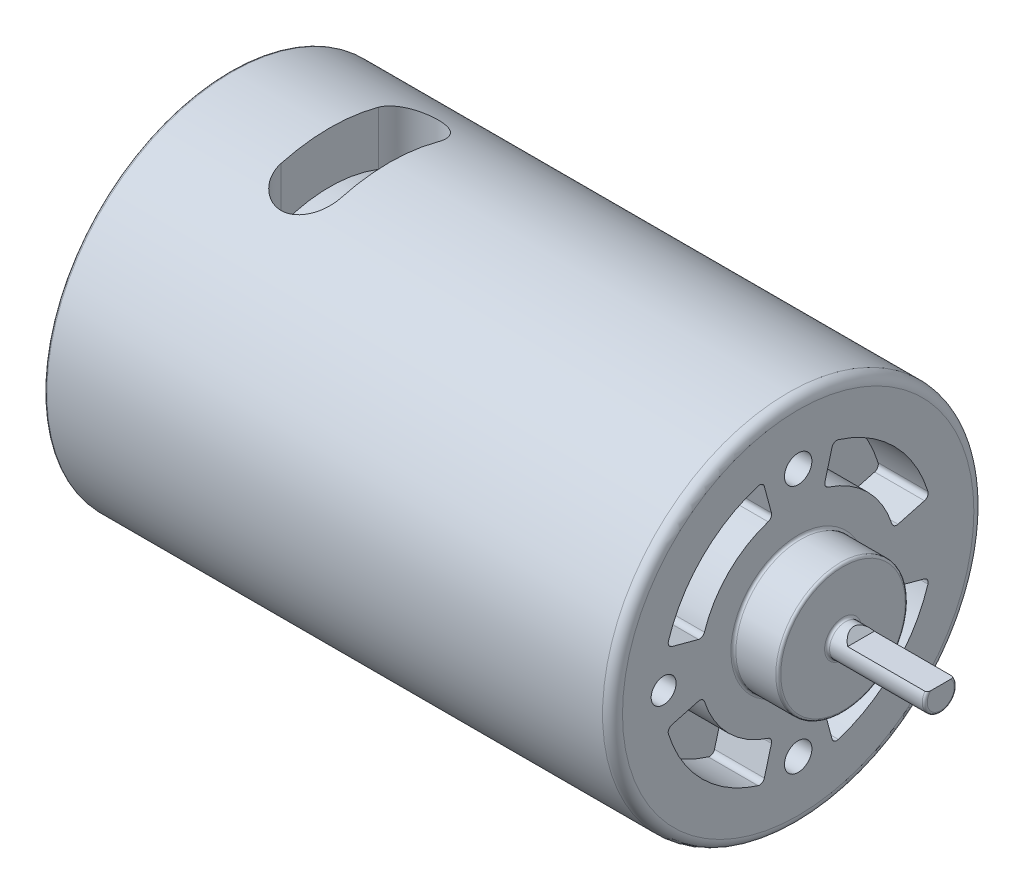
SolidWorks part; units mm, degrees
ref_plane "Front Plane" through (0, 0, 0) normal (0, 0, 1) x (1, 0, 0)
ref_plane "Top Plane" through (0, 0, 0) normal (0, 1, 0) x (1, 0, 0)
ref_plane "Right Plane" through (0, 0, 0) normal (1, 0, 0) x (0, 0, -1)
sketch "Sketch1" plane through (0, 0, 0) normal (0, 0, 1) x (1, 0, 0)
  line L0 (56.3322, 0) -> (-56.3322, 0) construction
  line L1 (37.9, 0) -> (37.9, 1.6)
  line L2 (37.9, 1.6) -> (28.1, 1.6)
  line L3 (28.1, 1.6) -> (28.1, 6.5)
  line L4 (28.1, 6.5) -> (23.6, 6.5)
  line L5 (23.6, 6.5) -> (23.6, 18.625)
  line L6 (23.6, 18.625) -> (-33.4, 18.625)
  line L7 (-33.4, 18.625) -> (-33.4, 5.125)
  line L8 (-33.4, 5.125) -> (-35.65, 5.125)
  line L9 (-35.65, 5.125) -> (-36.4, 4.5)
  line L10 (-36.4, 4.5) -> (-36.4, 1.6)
  line L11 (-36.4, 1.6) -> (-37.9, 1.6)
  line L12 (-37.9, 1.6) -> (-37.9, 0)
  line L13 (-37.9, 0) -> (37.9, 0)
  dimension "D1" = 9.8
  dimension "D2" = 4.5
  dimension "D3" = 1.5
  dimension "D4" = 0.75
  dimension "D5" = 3
  dimension "D6" = 57
  dimension "D7" = 1.6
  dimension "D8" = 6.5
  dimension "D9" = 18.625
  dimension "D10" = 5.125
  dimension "D11" = 1.6
  dimension "D12" = 4.5
revolve "Revolve1" add sketch "Sketch1" angle 360 about L0
fillet "Fillet1" radius 1 1 edges at (23.6, 18.625, 0)
fillet "Fillet2" radius 0.25 9 edges at (-37.9, 1.6, 0) (-36.4, 1.6, 0) (-35.65, 5.125, 0) (-36.4, 4.5, 0) (-33.4, 18.625, 0) (23.6, 6.5, 0) (28.1, 6.5, 0) (28.1, 1.6, 0) (37.9, 1.6, 0)
sketch "Sketch2" plane through (37.9, 0, 0) normal (1, 0, 0) x (0, 0, -1)
  line L0 (-1.7984, 0.875) -> (1.7984, 0.875)
  arc A1 (-1.7984, 0.875) -> (1.7984, 0.875) centre (0, 0) cw
  dimension "D2" = 2
  dimension "D1" = 0.875
extrude "Cut-Extrude1" cut sketch "Sketch2" against normal blind 8
sketch "Sketch3" plane through (0, 0, 0) normal (0, 0, 1) x (1, 0, 0)
  line L0 (29.9, 0.875) -> (29.175, 1.6)
  line L1 (29.9, 1.6) -> (28.35, 1.6) construction
  line L2 (29.175, 1.6) -> (29.9, 1.6)
  line L3 (29.9, 0.875) -> (29.9, 1.6) construction
  line L4 (29.9, 1.6) -> (29.9, 0.875)
  dimension "D1" = 45
extrude "Cut-Extrude2" cut sketch "Sketch3" against normal mid plane 8
sketch "Sketch4" plane through (0, 0, 0) normal (0, 1, 0) x (1, 0, 0)
  line L0 (0, 0) -> (-33.4, 0) construction
  line L1 (-33.4, 5.125) -> (-33.4, -5.125) construction
  line L2 (-20.4, 4.875) -> (-20.4, -4.875) construction
  line L3 (-33.4, 18.375) -> (-33.4, -18.375) construction
  line L4 (-23.4, 4.875) -> (-23.4, -4.875)
  line L5 (-17.4, 4.875) -> (-17.4, -4.875)
  arc A0 (-23.4, 4.875) -> (-17.4, 4.875) centre (-20.4, 4.875) cw
  arc A1 (-23.4, -4.875) -> (-17.4, -4.875) centre (-20.4, -4.875) ccw
  point P7 (-20.4, 0)
  dimension "D1" = 13
  dimension "D2" = 9.75
  dimension "D3" = 3
  dimension "D4" = 3
extrude "Cut-Extrude3" cut sketch "Sketch4" against normal mid plane 50
sketch "Sketch5" plane through (23.6, 0, 0) normal (1, 0, 0) x (0, 0, -1)
  line L0 (-4.8205, 17.9904) -> (4.8205, -17.9904) construction
  line L1 (4.8205, 17.9904) -> (-4.8205, -17.9904) construction
  line L2 (-17.9904, 4.8205) -> (17.9904, -4.8205) construction
  line L3 (17.9904, 4.8205) -> (-17.9904, -4.8205) construction
  line L4 (0, 18.625) -> (0, -18.625) construction
  line L5 (-18.625, 0) -> (18.625, 0) construction
  line L6 (-3.3945, 12.6686) -> (-2.6821, 10.0098)
  line L7 (3.3945, 12.6686) -> (2.6821, 10.0098)
  line L8 (10.0098, 2.6821) -> (12.6686, 3.3945)
  line L9 (10.0098, -2.6821) -> (12.6686, -3.3945)
  line L10 (3.3945, -12.6686) -> (2.6821, -10.0098)
  line L11 (-2.6821, -10.0098) -> (-3.3945, -12.6686)
  line L12 (-10.0098, -2.6821) -> (-12.6686, -3.3945)
  line L13 (-10.0098, 2.6821) -> (-12.6686, 3.3945)
  circle A0 centre (0, 0) radius 11.75 construction
  arc A1 (-13.0168, -4.0252) -> (-4.0252, -13.0168) centre (0, 0) ccw
  arc A2 (-9.4043, -3.0126) -> (-3.0126, -9.4043) centre (0, 0) ccw
  circle A3 centre (0, 0) radius 18.625 construction
  arc A4 (-3.0126, 9.4043) -> (-9.4043, 3.0126) centre (0, 0) ccw
  circle A5 centre (0, 0) radius 13.625 construction
  circle A6 centre (0, 0) radius 9.875 construction
  arc A7 (-4.0252, 13.0168) -> (-13.0168, 4.0252) centre (0, 0) ccw
  arc A8 (13.0168, 4.0252) -> (4.0252, 13.0168) centre (0, 0) ccw
  arc A9 (9.4043, 3.0126) -> (3.0126, 9.4043) centre (0, 0) ccw
  arc A10 (4.0252, -13.0168) -> (13.0168, -4.0252) centre (0, 0) ccw
  arc A11 (3.0126, -9.4043) -> (9.4043, -3.0126) centre (0, 0) ccw
  arc A12 (-10.0098, -2.6821) -> (-9.4043, -3.0126) centre (-9.8804, -3.1651) cw
  arc A13 (-12.6686, -3.3945) -> (-13.0168, -4.0252) centre (-12.5392, -3.8775) ccw
  arc A14 (-3.3945, -12.6686) -> (-4.0252, -13.0168) centre (-3.8775, -12.5392) cw
  arc A15 (-2.6821, -10.0098) -> (-3.0126, -9.4043) centre (-3.1651, -9.8804) ccw
  arc A16 (2.6821, -10.0098) -> (3.0126, -9.4043) centre (3.1651, -9.8804) cw
  arc A17 (3.3945, -12.6686) -> (4.0252, -13.0168) centre (3.8775, -12.5392) ccw
  arc A18 (12.6686, -3.3945) -> (13.0168, -4.0252) centre (12.5392, -3.8775) cw
  arc A19 (10.0098, -2.6821) -> (9.4043, -3.0126) centre (9.8804, -3.1651) ccw
  arc A20 (10.0098, 2.6821) -> (9.4043, 3.0126) centre (9.8804, 3.1651) cw
  arc A21 (12.6686, 3.3945) -> (13.0168, 4.0252) centre (12.5392, 3.8775) ccw
  arc A22 (3.3945, 12.6686) -> (4.0252, 13.0168) centre (3.8775, 12.5392) cw
  arc A23 (2.6821, 10.0098) -> (3.0126, 9.4043) centre (3.1651, 9.8804) ccw
  arc A24 (-3.3945, 12.6686) -> (-4.0252, 13.0168) centre (-3.8775, 12.5392) ccw
  arc A25 (-2.6821, 10.0098) -> (-3.0126, 9.4043) centre (-3.1651, 9.8804) cw
  arc A26 (-10.0098, 2.6821) -> (-9.4043, 3.0126) centre (-9.8804, 3.1651) ccw
  arc A27 (-12.6686, 3.3945) -> (-13.0168, 4.0252) centre (-12.5392, 3.8775) cw
  point P4 (9.875, 0)
  point P37 (13.625, 0)
  point P41 (-9.5385, -2.5558)
  point P44 (-13.1607, -3.5264)
  point P47 (-3.5264, -13.1607)
  point P50 (-2.5558, -9.5385)
  point P53 (2.5558, -9.5385)
  point P56 (3.5264, -13.1607)
  point P59 (13.1607, -3.5264)
  point P62 (9.5385, -2.5558)
  point P65 (9.5385, 2.5558)
  point P68 (13.1607, 3.5264)
  point P71 (3.5264, 13.1607)
  point P74 (2.5558, 9.5385)
  point P77 (-3.5264, 13.1607)
  point P80 (-2.5558, 9.5385)
  point P83 (-9.5385, 2.5558)
  point P86 (-13.1607, 3.5264)
  dimension "D1" = 23.5
  dimension "D8" = 0.5
  dimension "D4" = 15
  dimension "D5" = 15
  dimension "D6" = 15
  dimension "D7" = 15
  dimension "D2" = 1.875
  dimension "D3" = 1.875
extrude "Cut-Extrude4" cut sketch "Sketch5" against normal blind 5
sketch "Sketch6" plane through (23.6, 0, 0) normal (1, 0, 0) x (0, 0, -1)
  line L0 (0, 18.625) -> (0, -18.625) construction
  circle A0 centre (0, 0) radius 12.5 construction
  circle A1 centre (0, 0) radius 18.625 construction
  circle A2 centre (0, 12.5) radius 1.375
  circle A3 centre (0, -12.5) radius 1.375
  circle A4 centre (0, 0) radius 13.5 construction
  circle A5 centre (-13.5, 0) radius 1.25
  dimension "D1" = 25
  dimension "D2" = 2.75
  dimension "D3" = 27
  dimension "D4" = 2.5
extrude "Cut-Extrude5" cut sketch "Sketch6" against normal blind 5
sketch "Sketch7" plane through (-33.4, 0, 0) normal (-1, 0, 0) x (0, 0, 1)
  line L0 (-3.2342, 18.342) -> (3.2342, -18.342) construction
  line L1 (-3.2342, -18.342) -> (3.2342, 18.342) construction
  line L2 (17.5018, 6.3701) -> (-17.5018, -6.3701) construction
  line L3 (-17.5018, 6.3701) -> (17.5018, -6.3701) construction
  line L4 (0, 18.625) -> (0, -18.625) construction
  line L5 (-18.625, 0) -> (18.625, 0) construction
  line L6 (-1.6908, 9.5892) -> (-1.43, 8.1097)
  line L7 (1.6908, 9.5892) -> (1.43, 8.1097)
  line L8 (9.1499, 3.3303) -> (7.7382, 2.8165)
  line L9 (9.1499, -3.3303) -> (7.7382, -2.8165)
  line L10 (1.6908, -9.5892) -> (1.43, -8.1097)
  line L11 (-1.43, -8.1097) -> (-1.6908, -9.5892)
  line L12 (-9.1499, -3.3303) -> (-7.7382, -2.8165)
  line L13 (-9.1499, 3.3303) -> (-7.7382, 2.8165)
  circle A0 centre (0, 0) radius 9 construction
  arc A1 (-9.4394, -3.995) -> (-2.2952, -9.9897) centre (0, 0) ccw
  arc A2 (-7.1086, -3.0872) -> (-1.8059, -7.5367) centre (0, 0) ccw
  circle A3 centre (0, 0) radius 18.625 construction
  arc A4 (2.2952, -9.9897) -> (9.4394, -3.995) centre (0, 0) ccw
  circle A5 centre (0, 0) radius 10.25 construction
  circle A6 centre (0, 0) radius 7.75 construction
  arc A7 (1.8059, -7.5367) -> (7.1086, -3.0872) centre (0, 0) ccw
  arc A8 (9.4394, 3.995) -> (2.2952, 9.9897) centre (0, 0) ccw
  arc A9 (7.1086, 3.0872) -> (1.8059, 7.5367) centre (0, 0) ccw
  arc A10 (-2.2952, 9.9897) -> (-9.4394, 3.995) centre (0, 0) ccw
  arc A11 (-1.8059, 7.5367) -> (-7.1086, 3.0872) centre (0, 0) ccw
  arc A12 (-7.7382, -2.8165) -> (-7.1086, -3.0872) centre (-7.5672, -3.2863) cw
  arc A13 (-9.1499, -3.3303) -> (-9.4394, -3.995) centre (-8.9789, -3.8002) ccw
  arc A14 (-1.6908, -9.5892) -> (-2.2952, -9.9897) centre (-2.1832, -9.5024) cw
  arc A15 (-1.43, -8.1097) -> (-1.8059, -7.5367) centre (-1.9224, -8.0229) ccw
  arc A16 (1.43, -8.1097) -> (1.8059, -7.5367) centre (1.9224, -8.0229) cw
  arc A17 (1.6908, -9.5892) -> (2.2952, -9.9897) centre (2.1832, -9.5024) ccw
  arc A18 (9.1499, -3.3303) -> (9.4394, -3.995) centre (8.9789, -3.8002) cw
  arc A19 (7.7382, -2.8165) -> (7.1086, -3.0872) centre (7.5672, -3.2863) ccw
  arc A20 (7.7382, 2.8165) -> (7.1086, 3.0872) centre (7.5672, 3.2863) cw
  arc A21 (9.1499, 3.3303) -> (9.4394, 3.995) centre (8.9789, 3.8002) ccw
  arc A22 (1.43, 8.1097) -> (1.8059, 7.5367) centre (1.9224, 8.0229) ccw
  arc A23 (1.6908, 9.5892) -> (2.2952, 9.9897) centre (2.1832, 9.5024) cw
  arc A24 (-1.6908, 9.5892) -> (-2.2952, 9.9897) centre (-2.1832, 9.5024) ccw
  arc A25 (-1.43, 8.1097) -> (-1.8059, 7.5367) centre (-1.9224, 8.0229) cw
  arc A26 (-7.7382, 2.8165) -> (-7.1086, 3.0872) centre (-7.5672, 3.2863) ccw
  arc A27 (-9.1499, 3.3303) -> (-9.4394, 3.995) centre (-8.9789, 3.8002) cw
  circle A28 centre (-9, 0) radius 1.125
  circle A29 centre (9, 0) radius 1.125
  point P4 (7.75, 0)
  point P38 (10.25, 0)
  point P42 (-7.2826, -2.6507)
  point P45 (-9.6318, -3.5057)
  point P48 (-1.7799, -10.0943)
  point P51 (-1.3458, -7.6323)
  point P54 (1.3458, -7.6323)
  point P57 (1.7799, -10.0943)
  point P60 (9.6318, -3.5057)
  point P63 (7.2826, -2.6507)
  point P66 (7.2826, 2.6507)
  point P69 (9.6318, 3.5057)
  point P72 (1.3458, 7.6323)
  point P75 (1.7799, 10.0943)
  point P78 (-1.7799, 10.0943)
  point P81 (-1.3458, 7.6323)
  point P84 (-7.2826, 2.6507)
  point P87 (-9.6318, 3.5057)
  dimension "D1" = 18
  dimension "D8" = 0.5
  dimension "D9" = 2.25
  dimension "D4" = 10
  dimension "D5" = 10
  dimension "D6" = 20
  dimension "D7" = 20
  dimension "D2" = 1.25
  dimension "D3" = 1.25
extrude "Cut-Extrude6" cut sketch "Sketch7" against normal blind 5
sketch "Sketch8" plane through (0, 0, 0) normal (0, 0, 1) x (1, 0, 0)
  line L0 (0, 0) -> (-37.9, 0) construction
  line L1 (-37.9, 1.35) -> (-37.9, -1.35) construction
  line L2 (-29.9, 0) -> (-29.9, 13.5)
  line L3 (-29.9, 13.5) -> (0, 13.5)
  line L4 (0, 13.5) -> (0, 0)
  line L5 (-33.4, 18.375) -> (-33.4, -18.375) construction
  line L6 (-29.9, 0) -> (0, 0)
  dimension "D1" = 13.5
  dimension "D2" = 3.5
revolve "Revolve2" add sketch "Sketch8" angle 360 about L0
sketch "Sketch9" plane through (-33.4, 0, 0) normal (-1, 0, 0) x (0, 0, 1)
  line L0 (0, 14.25) -> (0, -14.25) construction
  line L1 (-2, 14.75) -> (2, 14.75)
  line L2 (-3, 12.75) -> (3, 12.75)
  line L3 (-3, 12.75) -> (-3, 15.75)
  line L4 (-3, 15.75) -> (3, 15.75)
  line L5 (3, 12.75) -> (3, 15.75)
  line L6 (-3, 12.75) -> (3, 15.75) construction
  line L7 (-3, 15.75) -> (3, 12.75) construction
  line L8 (-3, -15.75) -> (3, -15.75)
  line L9 (-3, -15.75) -> (-3, -12.75)
  line L10 (-3, -12.75) -> (3, -12.75)
  line L11 (3, -15.75) -> (3, -12.75)
  line L12 (-3, -15.75) -> (3, -12.75) construction
  line L13 (-3, -12.75) -> (3, -15.75) construction
  line L14 (2, 13.75) -> (2, 14.75)
  line L15 (-2, 13.75) -> (2, 13.75)
  line L16 (-2, 13.75) -> (-2, 14.75)
  line L17 (-2, -13.75) -> (2, -13.75)
  line L18 (2, -14.75) -> (2, -13.75)
  line L19 (-2, -14.75) -> (2, -14.75)
  line L20 (-2, -14.75) -> (-2, -13.75)
  circle A0 centre (0, 0) radius 14.25 construction
  dimension "D1" = 28.5
  dimension "D2" = 6
  dimension "D3" = 3
  dimension "D4" = 6
  dimension "D5" = 3
  dimension "D6" = 1
  dimension "D7" = 1
extrude "Boss-Extrude1" add sketch "Sketch9" along normal blind 1.25
fillet "Fillet3" radius 0.25 8 edges at (-34.65, -14.25, -3) (-34.65, -15.75, 0) (-34.65, -14.25, 3) (-34.65, -12.75, 0) (-34.65, 14.25, -3) (-34.65, 12.75, 0) (-34.65, 14.25, 3) (-34.65, 15.75, 0)
